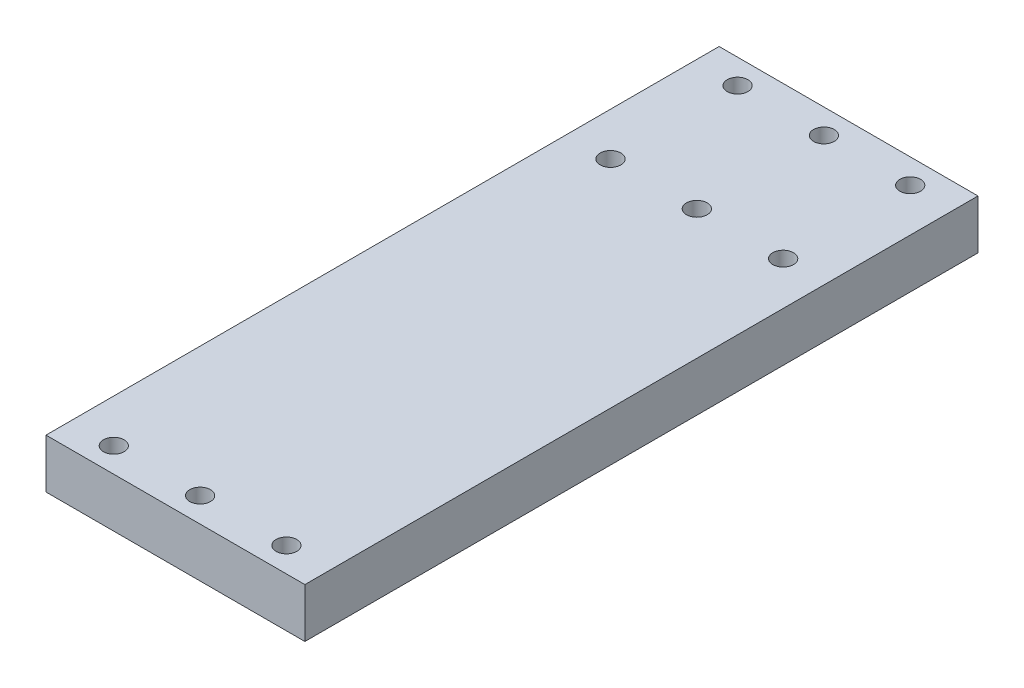
SolidWorks part; units mm, degrees
ref_plane "Front Plane" through (0, 0, 0) normal (0, 0, 1) x (1, 0, 0)
ref_plane "Top Plane" through (0, 0, 0) normal (0, 1, 0) x (1, 0, 0)
ref_plane "Right Plane" through (0, 0, 0) normal (1, 0, 0) x (0, 0, -1)
sketch "Sketch2" plane through (0, 0, 0) normal (0, 1, 0) x (1, 0, 0)
  line L1 (-25, -65) -> (25, -65)
  line L2 (-25, -65) -> (-25, 65)
  line L3 (-25, 65) -> (25, 65)
  line L4 (25, -65) -> (25, 65)
  line L5 (-25, -65) -> (25, 65) construction
  line L6 (-25, 65) -> (25, -65) construction
  point P0 (0, 0)
  dimension "D1" = 130
  dimension "D2" = 50
extrude "Boss-Extrude1" add sketch "Sketch2" along normal blind 9.525
sketch "Sketch3" plane through (0, 9.525, 0) normal (0, 1, 0) x (1, 0, 0)
  circle A0 centre (-16.67, -60.2375) radius 1.65 construction
  circle A1 centre (0, -60.2375) radius 1.65 construction
  circle A2 centre (16.67, -60.2375) radius 1.65 construction
  circle A3 centre (-16.67, 35.7) radius 2 construction
  circle A4 centre (0, 35.7) radius 2 construction
  circle A5 centre (16.67, 35.7) radius 2 construction
  circle A6 centre (-16.67, 60.2375) radius 2 construction
  circle A7 centre (0, 60.2375) radius 2 construction
  circle A8 centre (16.67, 60.2375) radius 2 construction
  circle A9 centre (-16.67, -60.2375) radius 1.65 construction
  circle A10 centre (0, -60.2375) radius 1.65 construction
  circle A11 centre (16.67, -60.2375) radius 1.65 construction
  circle A12 centre (-16.67, 35.7) radius 2 construction
  circle A13 centre (0, 35.7) radius 2 construction
  circle A14 centre (16.67, 35.7) radius 2 construction
  circle A15 centre (-16.67, 60.2375) radius 2 construction
  circle A16 centre (0, 60.2375) radius 2 construction
  circle A17 centre (16.67, 60.2375) radius 2 construction
  point P28 (-16.67, -60.2375)
  point P29 (0, -60.2375)
  point P30 (16.67, -60.2375)
  point P31 (-16.67, 35.7)
  point P32 (0, 35.7)
  point P33 (16.67, 35.7)
  point P34 (-16.67, 60.2375)
  point P35 (0, 60.2375)
  point P36 (16.67, 60.2375)
hole_wizard "Ø4.0mm Dowel Hole1" positions "Sketch3" profile "Sketch4" hole size "Ø4.0" standard "ANSI Metric" end condition through all
sketch "Sketch4" plane through (16.67, 9.525, -60.2375) normal (1, 0, 0) x (0, 0, 1)
  line L0 (0, 0) -> (0, 9.525)
  line L1 (0, 9.525) -> (2, 9.525)
  line L2 (2, 9.525) -> (2, 0)
  line L5 (2, 0) -> (0, 0)
  line L11 (0, -6.35) -> (0, 107.95) construction
  dimension "Thru Hole Dia." = 4
  dimension "Thru Hole Depth" = 9.525
